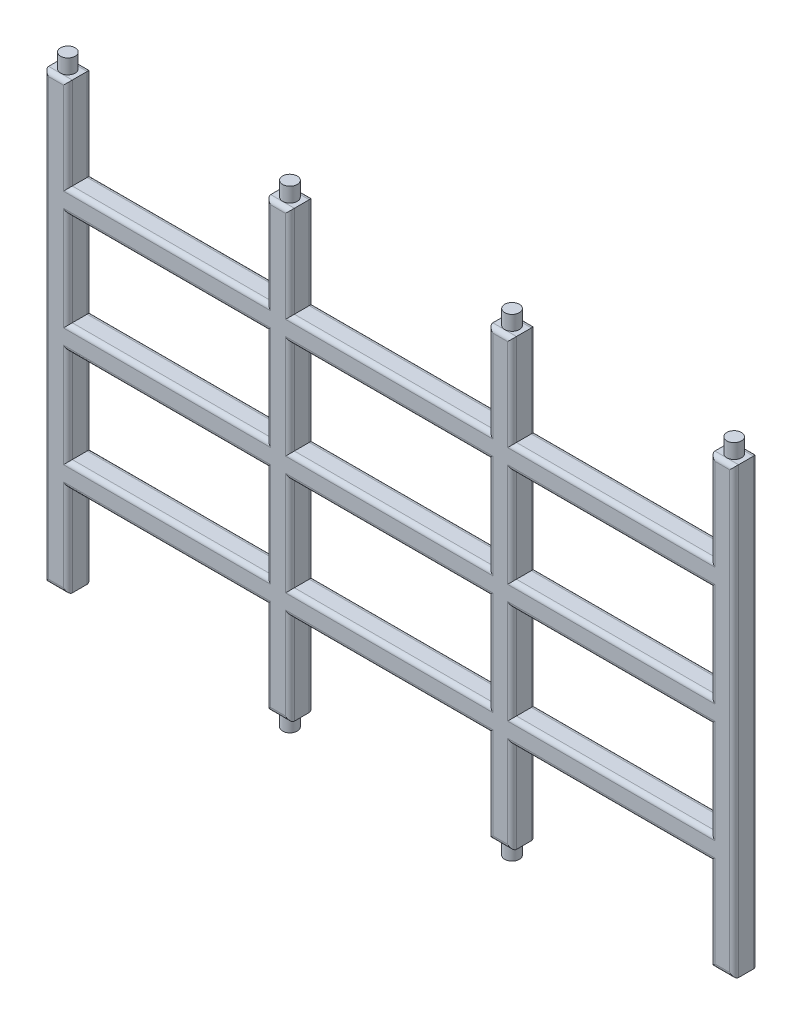
SolidWorks part; units mm, degrees
ref_plane "前视基准面" through (0, 0, 0) normal (0, 0, 1) x (1, 0, 0)
ref_plane "上视基准面" through (0, 0, 0) normal (0, 1, 0) x (1, 0, 0)
ref_plane "右视基准面" through (0, 0, 0) normal (1, 0, 0) x (0, 0, -1)
sketch "草图1" plane through (0, 0, 0) normal (0, 0, 1) x (1, 0, 0)
  line L0 (75, 150) -> (75, 0)
  line L1 (0, 150) -> (8, 150)
  line L2 (0, 150) -> (0, 0)
  line L3 (0, 0) -> (8, 0)
  line L4 (8, 150) -> (8, 0)
  line L5 (75, 150) -> (83, 150)
  line L6 (83, 150) -> (83, 0)
  line L7 (75, 0) -> (83, 0)
  line L8 (150, 150) -> (150, 0)
  line L9 (150, 150) -> (158, 150)
  line L10 (158, 150) -> (158, 0)
  line L11 (150, 0) -> (158, 0)
  line L12 (225, 150) -> (225, 0)
  line L13 (225, 150) -> (233, 150)
  line L14 (233, 150) -> (233, 0)
  line L15 (225, 0) -> (233, 0)
  line L16 (0, 79) -> (0, 71)
  line L17 (0, 119) -> (233, 119)
  line L18 (0, 119) -> (0, 111)
  line L19 (0, 111) -> (233, 111)
  line L20 (233, 119) -> (233, 111)
  line L21 (233, 79) -> (233, 71)
  line L22 (0, 71) -> (233, 71)
  line L23 (0, 79) -> (233, 79)
  line L24 (0, 39) -> (0, 31)
  line L25 (233, 39) -> (233, 31)
  line L26 (0, 31) -> (233, 31)
  line L27 (0, 39) -> (233, 39)
  point P23 (0, 75)
  point P30 (0, 75)
  dimension "D1" = 8
  dimension "D2" = 150
  dimension "D3" = 4
  dimension "D4" = 75
  dimension "D5" = 8
  dimension "D7" = 40
  dimension "D6" = 3
extrude "凸台-拉伸1" add sketch "草图1" along normal blind 8 contours L2 L17 L4 L1 | L4 L19 L0 L17 | L2 L19 L4 L17 | L2 L23 L4 L19 | L23 L4 L22 L0 | L2 L27 L4 L22 | L23 L2 L22 L4 | L27 L2 L26 L4 | L26 L2 L3 L4 | L27 L4 L26 L0 | L27 L0 L26 L6 | L26 L0 L7 L6 | L0 L27 L6 L22 | L23 L0 L22 L6 | L0 L23 L6 L19 | L0 L19 L6 L17 | L0 L17 L6 L5 | L6 L19 L8 L17 | L23 L6 L22 L8 | L27 L6 L26 L8 | L26 L8 L11 L10 | L27 L8 L26 L10 | L8 L27 L10 L22 | L23 L8 L22 L10 | L8 L23 L10 L19 | L8 L19 L10 L17 | L8 L17 L10 L9 | L10 L19 L12 L17 | L23 L10 L22 L12 | L27 L10 L26 L12 | L26 L12 L15 L14 | L27 L12 L26 L14 | L12 L27 L14 L22 | L23 L12 L22 L14 | L12 L23 L14 L19 | L12 L19 L14 L17 | L12 L17 L14 L13
sketch "草图2" plane through (0, 150, 0) normal (0, 1, 0) x (1, 0, 0)
  line L0 (233, 0) -> (225, 0) construction
  line L1 (225, 0) -> (225, -8) construction
  line L2 (225, -8) -> (233, -8) construction
  line L3 (233, -8) -> (233, 0) construction
  line L4 (158, 0) -> (150, 0) construction
  line L5 (150, 0) -> (150, -8) construction
  line L6 (150, -8) -> (158, -8) construction
  line L7 (158, -8) -> (158, 0) construction
  line L8 (83, 0) -> (75, 0) construction
  line L9 (75, 0) -> (75, -8) construction
  line L10 (75, -8) -> (83, -8) construction
  line L11 (83, -8) -> (83, 0) construction
  line L12 (8, 0) -> (0, 0) construction
  line L13 (0, 0) -> (0, -8) construction
  line L14 (0, -8) -> (8, -8) construction
  line L15 (8, -8) -> (8, 0) construction
  line L16 (233, 0) -> (225, 0)
  line L17 (225, 0) -> (225, -8)
  line L18 (225, -8) -> (233, -8)
  line L19 (233, -8) -> (233, 0)
  line L20 (158, 0) -> (150, 0)
  line L21 (150, 0) -> (150, -8)
  line L22 (150, -8) -> (158, -8)
  line L23 (158, -8) -> (158, 0)
  line L24 (83, 0) -> (75, 0)
  line L25 (75, 0) -> (75, -8)
  line L26 (75, -8) -> (83, -8)
  line L27 (83, -8) -> (83, 0)
  line L28 (8, 0) -> (0, 0)
  line L29 (0, 0) -> (0, -8)
  line L30 (0, -8) -> (8, -8)
  line L31 (8, -8) -> (8, 0)
  circle A0 centre (4, -4) radius 2.475
  circle A1 centre (79, -4) radius 2.475
  circle A2 centre (154, -4) radius 2.475
  circle A3 centre (229, -4) radius 2.475
  point P6 (0, 0)
  point P7 (4, 0)
  point P10 (0, -4)
  point P12 (0, 0)
  point P26 (0, 0)
  dimension "D1" = 4.95
  dimension "D3" = 75
  dimension "D2" = 4
extrude "凸台-拉伸3" add sketch "草图2" along normal blind 4.95 contours A0 | A3 | A1 | A2
sketch "草图3" plane through (0, 0, 0) normal (0, -1, 0) x (1, 0, 0)
  line L0 (-0.9937, 4) -> (8.6298, 4) construction
  line L1 (4, 8.4977) -> (4, -0.4756) construction
  line L4 (0, 0) -> (8, 0)
  line L5 (8, 0) -> (8, 8)
  line L6 (8, 8) -> (0, 8)
  line L7 (0, 8) -> (0, 0)
  line L8 (0, 0) -> (8, 0)
  line L9 (8, 0) -> (8, 8)
  line L10 (8, 8) -> (0, 8)
  line L11 (0, 8) -> (0, 0)
  circle A0 centre (4, 4) radius 2.475
  circle A1 centre (79, 4) radius 2.475
  circle A2 centre (154, 4) radius 2.475
  circle A3 centre (229, 4) radius 2.475
  point P6 (0, 4)
  point P9 (4, 8)
  dimension "D2" = 4.95
  dimension "D3" = 4
  dimension "D4" = 75
  dimension "D1" = 0
extrude "凸台-拉伸4" add sketch "草图3" along normal blind 4.95 contours A1 | A2
sketch "草图4" plane through (0, 0, 0) normal (0, -1, 0) x (1, 0, 0)
  line L0 (0, 8) -> (8, 8) construction
  line L1 (0, 8) -> (0, 0) construction
  circle A0 centre (4, 4) radius 2.525
  circle A1 centre (229, 4) radius 2.525
  dimension "D1" = 5.05
  dimension "D4" = 2
  dimension "D2" = 4
  dimension "D3" = 4
extrude "切除-拉伸1" cut sketch "草图4" against normal blind 15
fillet "圆角3" radius 1.5 104 edges at (158, 15.5, 8) (158, 15.5, 0) (154, 0, 0) (154, 0, 8) (150, 15.5, 8) (150, 15.5, 0) (116.5, 31, 8) (116.5, 31, 0) (83, 15.5, 8) (83, 15.5, 0) (79, 0, 0) (79, 0, 8) (75, 15.5, 8) (75, 15.5, 0) (41.5, 31, 8) (41.5, 31, 0) (8, 15.5, 8) (8, 15.5, 0) (4, 0, 0) (4, 0, 8) (0, 75, 0) (0, 75, 8) (4, 150, 0) (4, 150, 8) (8, 134.5, 8) (8, 134.5, 0) (41.5, 119, 8) (41.5, 119, 0) (75, 134.5, 8) (75, 134.5, 0) (79, 150, 0) (79, 150, 8) (83, 134.5, 8) (83, 134.5, 0) (116.5, 119, 8) (116.5, 119, 0) (150, 134.5, 8) (150, 134.5, 0) (154, 150, 0) (154, 150, 8) (158, 134.5, 8) (158, 134.5, 0) (191.5, 119, 8) (191.5, 119, 0) (225, 134.5, 8) (225, 134.5, 0) (229, 150, 0) (229, 150, 8) (233, 75, 0) (233, 75, 8) (229, 0, 0) (229, 0, 8) (225, 15.5, 8) (225, 15.5, 0) (191.5, 31, 8) (191.5, 31, 0) (116.5, 39, 8) (116.5, 39, 0) (83, 55, 8) (83, 55, 0) (116.5, 71, 8) (116.5, 71, 0) (150, 55, 8) (150, 55, 0) (116.5, 79, 8) (116.5, 79, 0) (83, 95, 8) (83, 95, 0) (116.5, 111, 8) (116.5, 111, 0) (150, 95, 8) (150, 95, 0) (41.5, 79, 8) (41.5, 79, 0) (8, 95, 8) (8, 95, 0) (41.5, 111, 8) (41.5, 111, 0) (75, 95, 8) (75, 95, 0) (41.5, 39, 8) (41.5, 39, 0) (8, 55, 8) (8, 55, 0) (41.5, 71, 8) (41.5, 71, 0) (75, 55, 8) (75, 55, 0) (191.5, 79, 8) (191.5, 79, 0) (158, 95, 8) (158, 95, 0) (191.5, 111, 8) (191.5, 111, 0) (225, 95, 8) (225, 95, 0) (191.5, 39, 8) (191.5, 39, 0) (158, 55, 8) (158, 55, 0) (191.5, 71, 8) (191.5, 71, 0) (225, 55, 8) (225, 55, 0)
